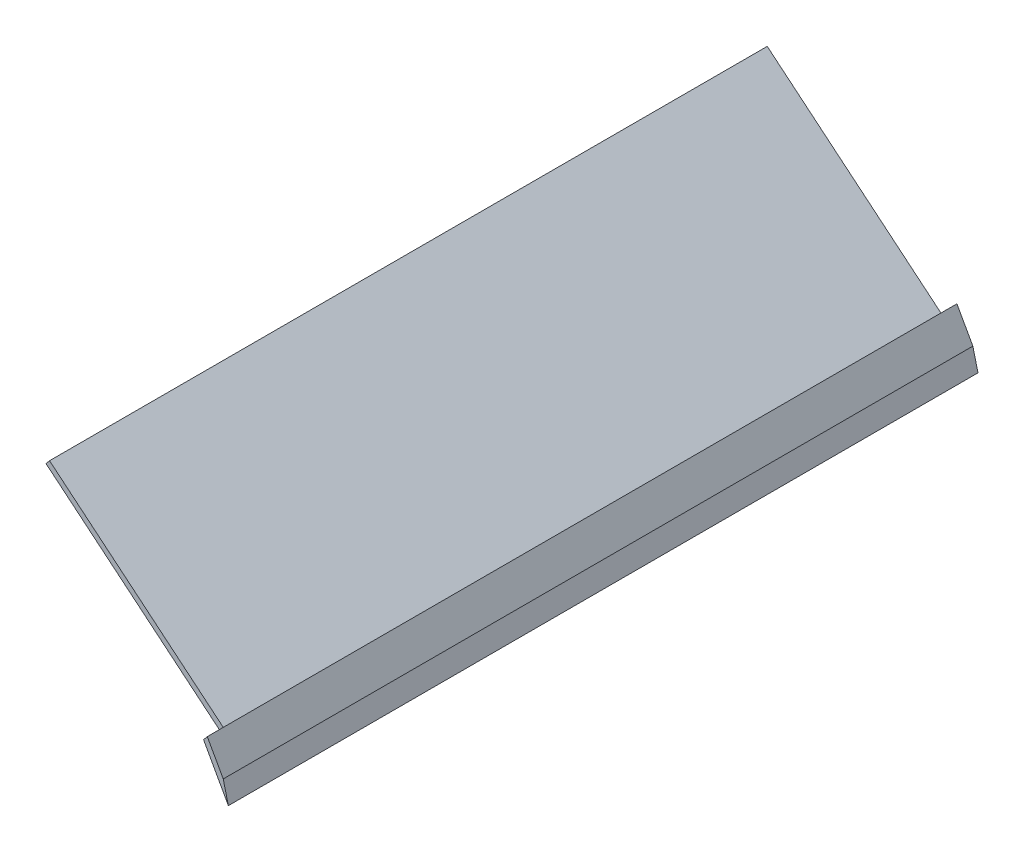
SolidWorks part; units mm, degrees
ref_plane "Alzado" through (0, 0, 0) normal (0, 0, 1) x (1, 0, 0)
ref_plane "Planta" through (0, 0, 0) normal (0, 1, 0) x (1, 0, 0)
ref_plane "Vista lateral" through (0, 0, 0) normal (1, 0, 0) x (0, 0, -1)
sketch "Sketch1" plane through (0, 0, 0) normal (0, 0, 1) x (1, 0, 0)
  line L0 (187.421, 132.7851) -> (137.5791, 174.1241)
  line L2 (137.5791, 174.1241) -> (138.6006, 175.3556)
  line L3 (188.6315, 133.8598) -> (138.6006, 175.3556)
  line L4 (187.421, 132.7851) -> (1.7215, 286.8047) construction
  line L5 (187.421, 132.7851) -> (194.7011, 119.6702)
  line L6 (188.6315, 133.8598) -> (193.2207, 125.5927)
  line L7 (194.7011, 119.6702) -> (193.2207, 125.5927)
  circle A0 centre (108.8822, 64.9326) radius 101.6 construction
  dimension "D1" = 1.6
  dimension "D2" = 65
  dimension "D3" = 15
  dimension "D4" = 15
  dimension "D5" = 1.58
extrude "Boss-Extrude1" add sketch "Sketch1" against normal up to surface (215.9 mm away)
sketch "Sketch2" plane through (142.6528, 171.9947, 0) normal (0.6384, 0.7697, 0) x (0.7697, -0.6384, 0)
  line L0 (-5.2646, 215.9) -> (-5.2646, 0) construction
  line L1 (-5.2646, 4.6) -> (59.7354, 4.6)
  line L2 (-5.2646, 4.6) -> (-5.2646, 0)
  line L3 (-5.2646, 0) -> (59.7354, 0)
  line L4 (59.7354, 4.6) -> (59.7354, 0)
  line L5 (59.7354, 215.9) -> (59.7354, 0) construction
  line L6 (-181.7703, 4.6) -> (59.4897, 4.6) construction
  line L7 (59.7354, 0) -> (-5.2646, 0) construction
  line L8 (73.4657, 107.95) -> (-101.9979, 107.95) construction
  line L9 (73.4657, 215.9) -> (73.4657, 0) construction
  line L10 (59.7354, 211.3) -> (59.7354, 215.9)
  line L11 (-5.2646, 215.9) -> (59.7354, 215.9)
  line L12 (-5.2646, 211.3) -> (-5.2646, 215.9)
  line L13 (-5.2646, 211.3) -> (59.7354, 211.3)
extrude "Cut-Extrude1" cut sketch "Sketch2" against normal through all
